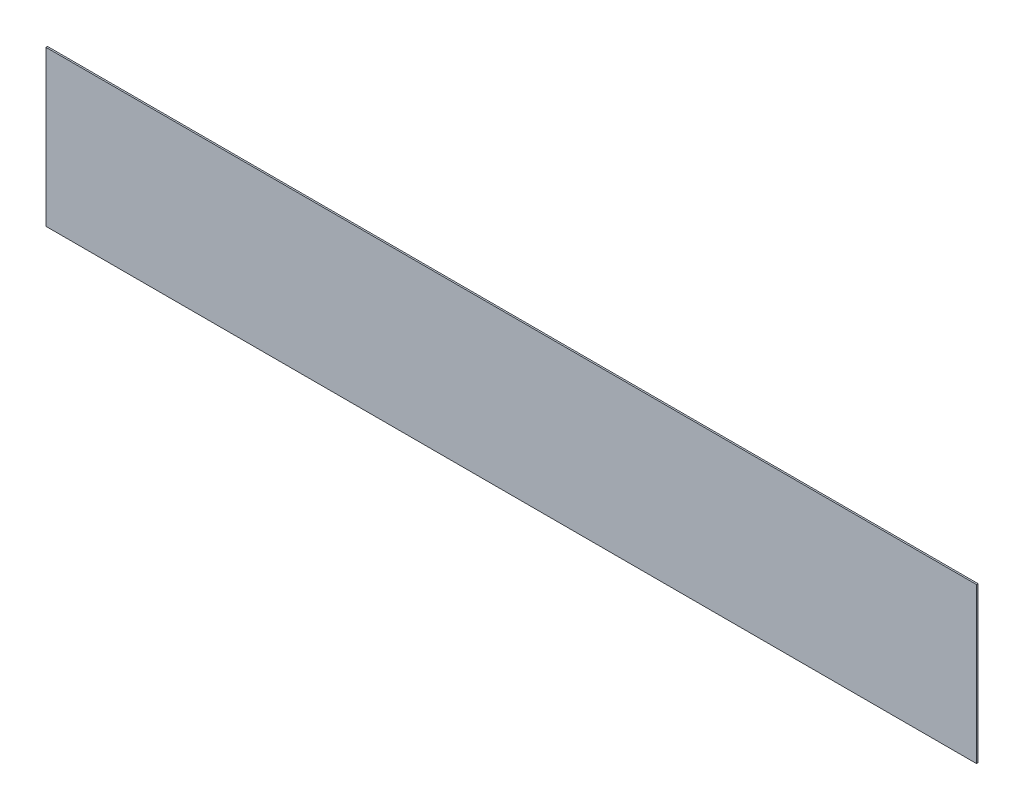
SolidWorks part; units mm, degrees
ref_plane "Front Plane" through (0, 0, 0) normal (0, 0, 1) x (1, 0, 0)
ref_plane "Top Plane" through (0, 0, 0) normal (0, 1, 0) x (1, 0, 0)
ref_plane "Right Plane" through (0, 0, 0) normal (1, 0, 0) x (0, 0, -1)
sketch "Sketch2" plane through (0, 0, 0) normal (0, 0, 1) x (1, 0, 0)
  line L0 (-3000, -500) -> (3000, -500)
  line L1 (-3000, -500) -> (-3000, 500)
  line L2 (-3000, 500) -> (3000, 500)
  line L3 (3000, -500) -> (3000, 500)
  line L4 (-3000, -500) -> (3000, 500) construction
  line L5 (-3000, 500) -> (3000, -500) construction
  point P0 (0, 0)
  point P5 (0, 0)
  dimension "D1" = 6000
  dimension "D2" = 1000
extrude "Boss-Extrude3" add sketch "Sketch2" along normal blind 10 contours L1 L2 L3 L0
